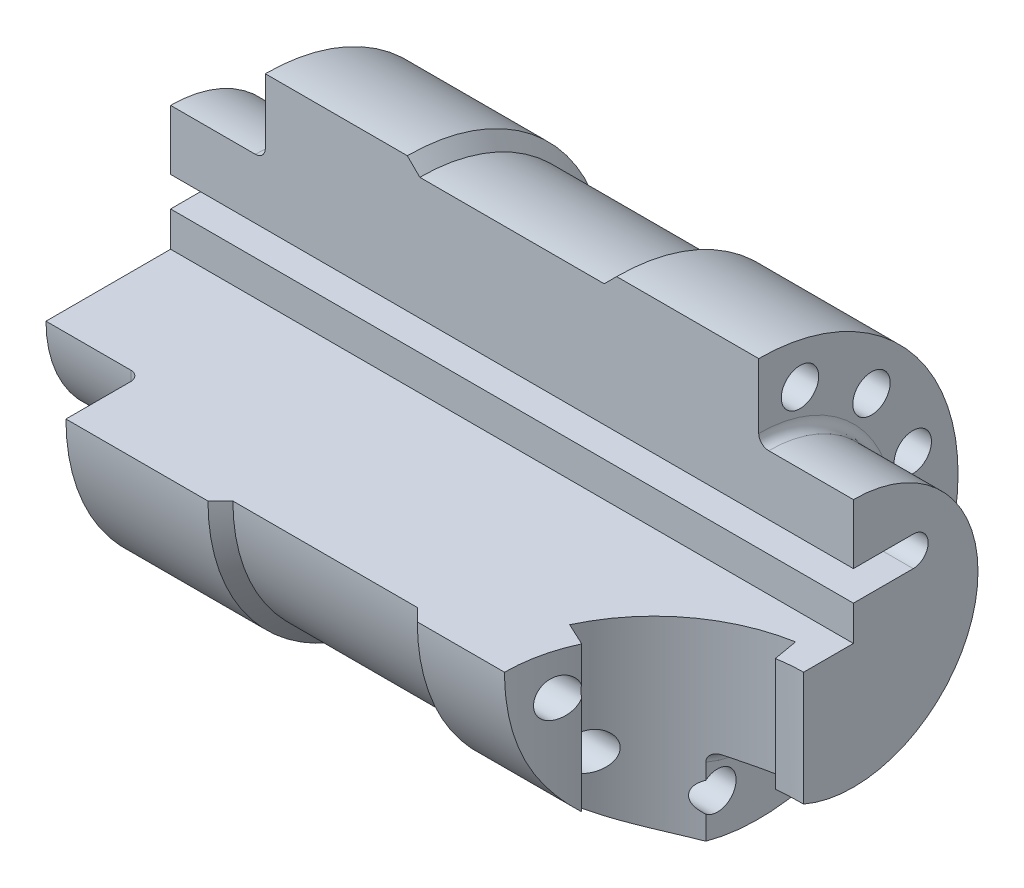
SolidWorks part; units mm, degrees
material "AISI 1020"
ref_plane "Plan de face" through (0, 0, 0) normal (0, 0, 1) x (1, 0, 0)
ref_plane "Plan de dessus" through (0, 0, 0) normal (0, 1, 0) x (1, 0, 0)
ref_plane "Plan de droite" through (0, 0, 0) normal (1, 0, 0) x (0, 0, -1)
sketch "Esquisse1" plane through (0, 0, 0) normal (0, 0, 1) x (1, 0, 0)
  line L0 (0, 0) -> (24.5663, 0)
  line L1 (24.5663, 0) -> (24.5663, 25)
  line L2 (24.5663, 25) -> (7.5663, 25)
  line L3 (5.5663, 27) -> (5.5663, 40)
  line L4 (5.5663, 40) -> (-22.9337, 40)
  line L5 (-22.9337, 40) -> (-25.4337, 37.5)
  line L6 (-25.4337, 37.5) -> (-62.4337, 37.5)
  line L7 (-62.4337, 37.5) -> (-64.9337, 40)
  line L8 (-64.9337, 40) -> (-93.4337, 40)
  line L9 (-93.4337, 40) -> (-93.4337, 27)
  line L10 (-95.4337, 25) -> (-112.4337, 25)
  line L11 (-112.4337, 25) -> (-112.4337, 0)
  line L12 (-112.4337, 0) -> (0, 0)
  line L13 (-130.7689, 0) -> (47.3428, 0) construction
  arc A0 (-95.4337, 25) -> (-93.4337, 27) centre (-95.4337, 27) ccw
  arc A1 (7.5663, 25) -> (5.5663, 27) centre (7.5663, 27) cw
  dimension "D11" = 2
  dimension "D13" = 2
  dimension "D1" = 25
  dimension "D2" = 40
  dimension "D3" = 19
  dimension "D4" = 19
  dimension "D5" = 28.5
  dimension "D6" = 28.5
  dimension "D7" = 2.5
  dimension "D8" = 2.5
  dimension "D9" = 225
  dimension "D10" = 225
  dimension "D12" = 25
  dimension "D14" = 137
revolve "Révolution1" add sketch "Esquisse1" angle 360 about L13
sketch "Esquisse2" plane through (-112.4337, 0, 0) normal (-1, 0, 0) x (0, 0, 1)
  line L0 (0, 0) -> (0, 7)
  line L1 (0, 0) -> (43.4498, 0)
  line L2 (0, 0) -> (0, 7)
  line L3 (0, 44.4974) -> (43.4498, 44.4974)
  line L4 (43.4498, 0) -> (43.4498, 44.4974)
  line L9 (0, 10) -> (-12, 10)
  line L10 (0, 10) -> (-12, 10) construction
  line L11 (0, 7) -> (-12, 7)
  line L12 (0, 13) -> (-12, 13)
  line L13 (0, 13) -> (0, 44.4974)
  arc A0 (0, 7) -> (0, 13) centre (0, 10) ccw
  arc A1 (-12, 13) -> (-12, 7) centre (-12, 10) ccw
  point P7 (-6, 10)
  dimension "D2" = 3
  dimension "D1" = 12
  dimension "D3" = 7
extrude "Enlèv. mat.-Extru.1" cut sketch "Esquisse2" against normal through all
sketch "Esquisse3" plane through (-93.4337, 0, 0) normal (-1, 0, 0) x (0, 0, 1)
  line L0 (0, 0) -> (-12.0134, 44.8348) construction
  line L1 (0, 13) -> (0, 25) construction
  line L2 (0, 0) -> (-8.2822, 30.9096) construction
  line L3 (0, 0) -> (-22.6274, 22.6274) construction
  circle A0 centre (0, 0) radius 32 construction
  circle A1 centre (-8.2822, 30.9096) radius 3.75
  circle A2 centre (-22.6274, 22.6274) radius 3.75
  circle A3 centre (-30.9096, 8.2822) radius 3.75
  circle A4 centre (-30.9096, -8.2822) radius 3.75
  circle A5 centre (-22.6274, -22.6274) radius 3.75
  circle A6 centre (-8.2822, -30.9096) radius 3.75
  circle A7 centre (8.2822, -30.9096) radius 3.75
  circle A8 centre (22.6274, -22.6274) radius 3.75
  circle A9 centre (30.9096, -8.2822) radius 3.75
  dimension "D1" = 64
  dimension "D2" = 7.5
  dimension "D3" = 15
  dimension "D5" = 30
  dimension "D4" = 9
extrude "Enlèv. mat.-Extru.2" cut sketch "Esquisse3" against normal through all
sketch "Esquisse4" plane through (0, 0, 0) normal (0, 1, 0) x (1, 0, 0)
  line L0 (24.5663, -25) -> (24.5663, -40) construction
  line L1 (5.5663, -40) -> (24.5663, -40) construction
  line L2 (24.5663, -40) -> (24.5663, -5)
  line L3 (24.5663, -40) -> (-10.4337, -40)
  line L4 (24.5663, -40) -> (-7.1545, -25.2084)
  line L5 (24.5663, -40) -> (18.4886, -5.5317)
  arc A0 (24.5663, -10) -> (-5.4337, -40) centre (24.5663, -40) ccw
  arc A1 (24.5663, -5) -> (-10.4337, -40) centre (24.5663, -40) ccw
  line M14 (5.5663, -40) -> (5.5663, -27)
  arc M15 (5.5663, -27) -> (7.5663, -25) centre (7.5663, -27) cw
  line M16 (7.5663, -25) -> (24.5663, -25)
  line M17 (24.5663, -25) -> (24.5663, 0)
  dimension "D1" = 70
  dimension "D2" = 60
  dimension "D3" = 10
  dimension "D4" = 25
extrude "Enlèv. mat.-Extru.3" cut sketch "Esquisse4" against normal through all contours L4 L5 M16 M15 M14 | L4 A0 L3 M14 | L5 A0 L4 M14 M15 M16 | L3 L4 M14 | L5 A1 L4 A0 | A0 L5 M17 M16 | L5 L2 M16
equation "\"A\"= 137"
equation "\"B\" = 19"
equation "\"C\" = 28.5"
equation "\"D3@Esquisse1\"=\"B\""
equation "\"D4@Esquisse1\"=\"B\""
equation "\"D5@Esquisse1\"=\"C\""
equation "\"D6@Esquisse1\"=\"C\""
equation "\"D14@Esquisse1\"=\"A\""
